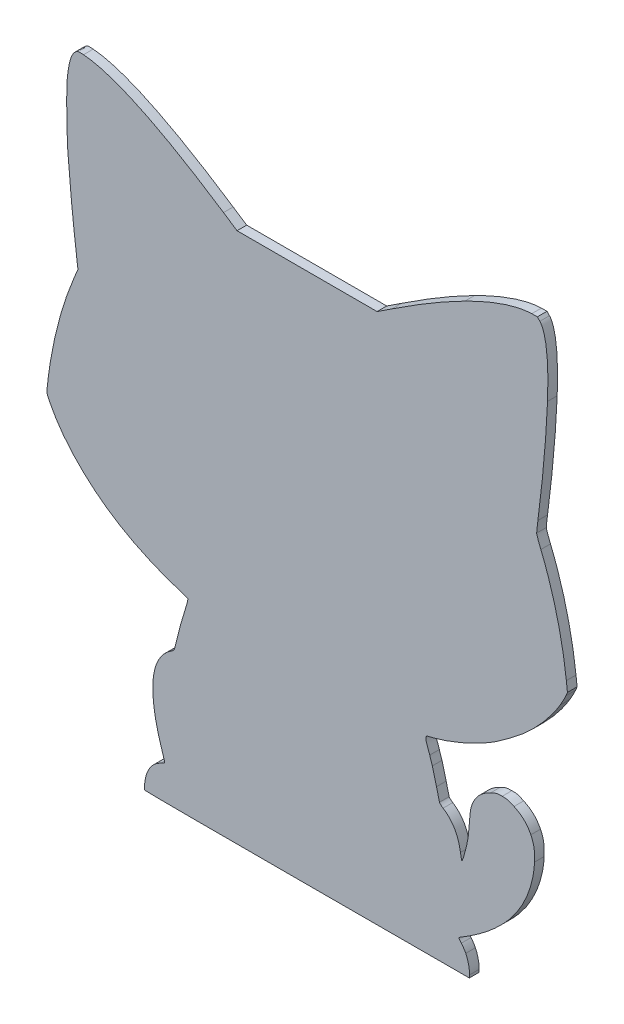
SolidWorks part; units mm, degrees
ref_plane "Front" through (0, 0, 0) normal (0, 0, 1) x (1, 0, 0)
ref_plane "Top" through (0, 0, 0) normal (0, 1, 0) x (1, 0, 0)
ref_plane "Right" through (0, 0, 0) normal (1, 0, 0) x (0, 0, -1)
sketch "Layer_3_board_outline" plane through (0, 0, 0) normal (0, 0, 1) x (1, 0, 0)
  line L0 (10.9053, 66.9894) -> (11.5659, 68.5759)
  line L1 (11.5659, 68.5759) -> (11.4685, 69.3451)
  line L3 (35.3096, 88.4796) -> (37.5166, 87.0182)
  line L4 (37.5166, 87.0182) -> (48.9356, 87.0182)
  line L5 (48.9356, 87.0182) -> (60.3546, 87.0182)
  line L6 (60.3546, 87.0182) -> (62.78, 88.6113)
  line L8 (85.5745, 99.329) -> (86.4912, 99.3449)
  line L9 (86.4912, 99.3449) -> (86.894, 98.9141)
  line L11 (91.2192, 50.3286) -> (91.3952, 48.7468)
  line L12 (91.3952, 48.7468) -> (91.1586, 48.1639)
  line L14 (71.6522, 32.0554) -> (70.4053, 31.6632)
  line L16 (75.4324, 0.8747) -> (75.3997, 0.419)
  line L17 (75.3997, 0.419) -> (48.9694, 0.3927)
  spline S0 degree 3 poles (22.5543, 2.0915) (22.8743, 3.7639) (23.7352, 4.9669) (25.0536, 5.5838) knots 0 0 0 0 1 1 1 1
  spline S1 degree 3 poles (25.0536, 5.5838) (25.4249, 5.7576) (25.7287, 5.9564) (25.7287, 6.0256) knots 0 0 0 0 1 1 1 1
  spline S2 degree 3 poles (25.7287, 6.0256) (25.7287, 6.0948) (25.5632, 6.6404) (25.3609, 7.238) knots 0 0 0 0 1 1 1 1
  spline S3 degree 3 poles (25.3609, 7.238) (25.1586, 7.8357) (24.8564, 8.8396) (24.6894, 9.469) knots 0 0 0 0 1 1 1 1
  spline S4 degree 3 poles (24.6894, 9.469) (22.9907, 15.8686) (23.6624, 20.1728) (26.6795, 22.2217) knots 0 0 0 0 1 1 1 1
  spline S5 degree 3 poles (26.6795, 22.2217) (27.344, 22.6729) (27.2709, 22.5103) (27.7511, 24.6043) knots 0 0 0 0 1 1 1 1
  spline S6 degree 3 poles (27.7511, 24.6043) (28.0842, 26.057) (28.3922, 27.1563) (29.0736, 29.3246) knots 0 0 0 0 1 1 1 1
  spline S7 degree 3 poles (29.0736, 29.3246) (29.3591, 30.233) (29.5542, 31.0103) (29.5071, 31.0519) knots 0 0 0 0 1 1 1 1
  spline S8 degree 3 poles (29.5071, 31.0519) (29.4601, 31.0936) (28.7194, 31.3501) (27.8612, 31.622) knots 0 0 0 0 1 1 1 1
  spline S9 degree 3 poles (27.8612, 31.622) (23.6426, 32.9585) (19.3544, 35.0396) (16.2626, 37.251) knots 0 0 0 0 1 1 1 1
  spline S10 degree 3 poles (16.2626, 37.251) (12.0986, 40.2293) (8.7842, 43.8871) (7.0331, 47.4367) knots 0 0 0 0 1 1 1 1
  spline S11 degree 3 poles (7.0331, 47.4367) (6.4891, 48.5393) (6.4706, 48.6047) (6.5317, 49.2058) knots 0 0 0 0 1 1 1 1
  spline S12 degree 3 poles (6.5317, 49.2058) (7.1759, 55.5391) (8.6742, 61.6314) (10.9053, 66.9894) knots 0 0 0 0 1 1 1 1
  spline S13 degree 3 poles (11.4685, 69.3451) (10.7624, 74.9222) (10.3512, 78.9367) (9.9139, 84.5216) knots 0 0 0 0 1 1 1 1
  spline S14 degree 3 poles (9.9139, 84.5216) (9.7349, 86.8074) (9.6665, 92.8149) (9.8014, 94.4038) knots 0 0 0 0 1 1 1 1
  spline S15 degree 3 poles (9.8014, 94.4038) (10.0299, 97.0971) (10.5123, 98.6644) (11.2695, 99.1737) knots 0 0 0 0 1 1 1 1
  spline S16 degree 3 poles (11.2695, 99.1737) (11.6019, 99.3972) (11.7071, 99.4131) (12.4782, 99.3562) knots 0 0 0 0 1 1 1 1
  spline S17 degree 3 poles (12.4782, 99.3562) (17.2568, 99.0032) (24.9562, 95.3353) (35.3096, 88.4796) knots 0 0 0 0 1 1 1 1
  spline S18 degree 3 poles (62.78, 88.6113) (67.6195, 91.7902) (70.9778, 93.7789) (74.6716, 95.6533) knots 0 0 0 0 1 1 1 1
  spline S19 degree 3 poles (74.6716, 95.6533) (79.313, 98.0086) (83.1023, 99.286) (85.5745, 99.329) knots 0 0 0 0 1 1 1 1
  spline S20 degree 3 poles (86.894, 98.9141) (87.9393, 97.7962) (88.385, 94.0098) (88.1512, 88.2336) knots 0 0 0 0 1 1 1 1
  spline S21 degree 3 poles (88.1512, 88.2336) (87.9441, 83.1197) (87.364, 76.6222) (86.5798, 70.6345) knots 0 0 0 0 1 1 1 1
  spline S22 degree 3 poles (86.5798, 70.6345) (86.4674, 69.7763) (86.3752, 68.9237) (86.3748, 68.7398) knots 0 0 0 0 1 1 1 1
  spline S23 degree 3 poles (86.3748, 68.7398) (86.3745, 68.5559) (86.6813, 67.6681) (87.0565, 66.7668) knots 0 0 0 0 1 1 1 1
  spline S24 degree 3 poles (87.0565, 66.7668) (89.0657, 61.9419) (90.602, 55.875) (91.2192, 50.3286) knots 0 0 0 0 1 1 1 1
  spline S25 degree 3 poles (91.1586, 48.1639) (91.0285, 47.8433) (90.5978, 47.0338) (90.2015, 46.3649) knots 0 0 0 0 1 1 1 1
  spline S26 degree 3 poles (90.2015, 46.3649) (88.3612, 43.2589) (85.3637, 40.0375) (82.1396, 37.7007) knots 0 0 0 0 1 1 1 1
  spline S27 degree 3 poles (82.1396, 37.7007) (81.5556, 37.2774) (80.7888, 36.7204) (80.4357, 36.4629) knots 0 0 0 0 1 1 1 1
  spline S28 degree 3 poles (80.4357, 36.4629) (79.3811, 35.6941) (78.2868, 35.0378) (76.8646, 34.3211) knots 0 0 0 0 1 1 1 1
  spline S29 degree 3 poles (76.8646, 34.3211) (75.1759, 33.4267) (73.4397, 32.6819) (71.6522, 32.0554) knots 0 0 0 0 1 1 1 1
  spline S30 degree 3 poles (70.4053, 31.6632) (69.7195, 31.4475) (68.9243, 31.2338) (68.6382, 31.1884) knots 0 0 0 0 1 1 1 1
  spline S31 degree 3 poles (68.6382, 31.1884) (67.9304, 31.0665) (68.5596, 29.7193) (68.94, 28.679) knots 0 0 0 0 1 1 1 1
  spline S32 degree 3 poles (68.94, 28.679) (68.9683, 28.4555) (69.2248, 27.8183) (69.3642, 27.3601) knots 0 0 0 0 1 1 1 1
  spline S33 degree 3 poles (69.3642, 27.3601) (69.5037, 26.9019) (69.8097, 25.7317) (70.0443, 24.7595) knots 0 0 0 0 1 1 1 1
  spline S34 degree 3 poles (70.0443, 24.7595) (70.2788, 23.7874) (70.4956, 22.9068) (70.526, 22.8027) knots 0 0 0 0 1 1 1 1
  spline S35 degree 3 poles (70.526, 22.8027) (70.5564, 22.6986) (70.8228, 22.457) (71.1181, 22.266) knots 0 0 0 0 1 1 1 1
  spline S36 degree 3 poles (71.1181, 22.266) (72.6744, 21.2587) (73.5873, 19.7014) (73.9538, 17.4287) knots 0 0 0 0 1 1 1 1
  spline S37 degree 3 poles (73.9538, 17.4287) (74.0412, 16.8863) (74.1326, 16.4227) (74.1568, 16.3985) knots 0 0 0 0 1 1 1 1
  spline S38 degree 3 poles (74.1568, 16.3985) (74.3156, 16.2397) (75.0624, 19.0086) (75.2337, 20.3914) knots 0 0 0 0 1 1 1 1
  spline S39 degree 3 poles (75.2337, 20.3914) (75.2975, 20.9063) (75.3914, 21.9859) (75.4424, 22.7904) knots 0 0 0 0 1 1 1 1
  spline S40 degree 3 poles (75.4424, 22.7904) (75.5123, 23.8944) (75.5975, 24.4329) (75.7897, 24.9855) knots 0 0 0 0 1 1 1 1
  spline S41 degree 3 poles (75.7897, 24.9855) (76.3222, 26.5169) (77.2683, 27.5376) (78.8636, 28.3018) knots 0 0 0 0 1 1 1 1
  spline S42 degree 3 poles (78.8636, 28.3018) (79.7849, 28.7432) (79.875, 28.7652) (80.7569, 28.7652) knots 0 0 0 0 1 1 1 1
  spline S43 degree 3 poles (80.7569, 28.7652) (81.6424, 28.7652) (81.7267, 28.7444) (82.6855, 28.2872) knots 0 0 0 0 1 1 1 1
  spline S44 degree 3 poles (82.6855, 28.2872) (84.0184, 27.6517) (84.8444, 26.8593) (85.4246, 25.6593) knots 0 0 0 0 1 1 1 1
  spline S45 degree 3 poles (85.4246, 25.6593) (85.9548, 24.563) (86.1083, 23.6615) (86.0304, 22.1023) knots 0 0 0 0 1 1 1 1
  spline S46 degree 3 poles (86.0304, 22.1023) (85.8531, 18.5534) (84.4733, 15.1028) (82.0199, 12.0731) knots 0 0 0 0 1 1 1 1
  spline S47 degree 3 poles (82.0199, 12.0731) (81.1603, 11.0116) (79.5673, 9.456) (78.2886, 8.4295) knots 0 0 0 0 1 1 1 1
  spline S48 degree 3 poles (78.2886, 8.4295) (77.2107, 7.564) (75.046, 6.0753) (74.1255, 5.5662) knots 0 0 0 0 1 1 1 1
  spline S49 degree 3 poles (74.1255, 5.5662) (73.8823, 5.4318) (73.6834, 5.2771) (73.6834, 5.2225) knots 0 0 0 0 1 1 1 1
  spline S50 degree 3 poles (73.6834, 5.2225) (73.6834, 5.1679) (73.8679, 4.923) (74.0935, 4.6783) knots 0 0 0 0 1 1 1 1
  spline S51 degree 3 poles (74.0935, 4.6783) (74.3191, 4.4335) (74.644, 3.9554) (74.8154, 3.6158) knots 0 0 0 0 1 1 1 1
  spline S52 degree 3 poles (74.8154, 3.6158) (75.173, 2.9074) (75.4802, 1.5425) (75.4324, 0.8747) knots 0 0 0 0 1 1 1 1
  spline S53 degree 3 poles (48.9694, 0.3927) (34.4327, 0.3783) (22.5078, 0.3978) (22.4315, 0.4741) knots 0 0 0 0 1 1 1 1
  spline S54 degree 3 poles (22.4315, 0.4741) (22.3552, 0.5504) (22.3902, 1.2336) (22.5543, 2.0915) knots 0 0 0 0 1 1 1 1
sketch "Layer_3_board_outline_dog" plane through (0, 0, 0) normal (0, 0, 1) x (1, 0, 0)
  line L0 (34.5113, 86.8831) -> (37.5166, 87.0182)
  line L1 (37.5166, 87.0182) -> (48.9356, 87.0182)
  line L2 (48.9356, 87.0182) -> (60.3546, 87.0182)
  line L3 (60.3546, 87.0182) -> (63.4286, 86.965)
  line L6 (70.4053, 31.6632) -> (71.6522, 32.0554)
  line L7 (75.4324, 0.8747) -> (75.3997, 0.419)
  line L8 (75.3997, 0.419) -> (48.9694, 0.3927)
  spline S0 degree 3 poles (22.5543, 2.0915) (22.8743, 3.7639) (23.7352, 4.9669) (25.0536, 5.5838) knots 0 0 0 0 1 1 1 1
  spline S1 degree 3 poles (25.0536, 5.5838) (25.4249, 5.7576) (25.7287, 5.9564) (25.7287, 6.0256) knots 0 0 0 0 1 1 1 1
  spline S2 degree 3 poles (25.7287, 6.0256) (25.7287, 6.0948) (25.5632, 6.6404) (25.3609, 7.238) knots 0 0 0 0 1 1 1 1
  spline S3 degree 3 poles (25.3609, 7.238) (25.1586, 7.8357) (24.8564, 8.8396) (24.6894, 9.469) knots 0 0 0 0 1 1 1 1
  spline S4 degree 3 poles (24.6894, 9.469) (22.9907, 15.8686) (23.6624, 20.1728) (26.6795, 22.2217) knots 0 0 0 0 1 1 1 1
  spline S5 degree 3 poles (26.6795, 22.2217) (27.344, 22.6729) (27.2709, 22.5103) (27.7511, 24.6043) knots 0 0 0 0 1 1 1 1
  spline S6 degree 3 poles (27.7511, 24.6043) (28.0842, 26.057) (28.3922, 27.1563) (29.0736, 29.3246) knots 0 0 0 0 1 1 1 1
  spline S7 degree 3 poles (29.0736, 29.3246) (29.3591, 30.233) (29.5542, 31.0103) (29.5071, 31.0519) knots 0 0 0 0 1 1 1 1
  spline S8 degree 3 poles (29.5071, 31.0519) (29.4601, 31.0936) (28.7194, 31.3501) (27.8612, 31.622) knots 0 0 0 0 1 1 1 1
  spline S9 degree 3 poles (27.8612, 31.622) (23.6426, 32.9585) (19.3544, 35.0396) (16.2626, 37.251) knots 0 0 0 0 1 1 1 1
  spline S10 degree 3 poles (16.2626, 37.251) (14.8605, 38.2539) (13.5547, 39.3338) (12.3724, 40.4607) knots 0 0 0 0 1 1 1 1
  spline S11 degree 3 poles (12.3724, 40.4607) (8.0865, 44.7253) (6.6138, 52.6467) (8.3368, 59.3063) knots 0 0 0 0 1 1 1 1
  spline S12 degree 3 poles (8.3368, 59.3063) (9.0353, 61.9873) (9.8952, 64.5636) (10.9053, 66.9894) knots 0 0 0 0 1 1 1 1
  spline S13 degree 3 poles (10.9053, 66.9894) (11.5659, 68.7009) (12.4282, 70.3216) (13.2396, 71.9644) knots 0 0 0 0 1 1 1 1
  spline S14 degree 3 poles (13.2396, 71.9644) (11.7395, 75.6682) (10.3159, 79.8187) (9.9139, 84.5216) knots 0 0 0 0 1 1 1 1
  spline S15 degree 3 poles (9.9139, 84.5216) (9.7923, 85.9446) (9.6966, 88.8136) (9.7305, 91.1579) knots 0 0 0 0 1 1 1 1
  spline S16 degree 3 poles (9.7305, 91.1579) (9.762, 93.3288) (10.4659, 95.1894) (12.6101, 96.8277) knots 0 0 0 0 1 1 1 1
  spline S17 degree 3 poles (12.6101, 96.8277) (15.0948, 98.5292) (17.1938, 98.3272) (19.1427, 97.5385) knots 0 0 0 0 1 1 1 1
  spline S18 degree 3 poles (19.1427, 97.5385) (23.4634, 95.771) (29.639, 90.4894) (34.5113, 86.8831) knots 0 0 0 0 1 1 1 1
  spline S19 degree 3 poles (63.4286, 86.965) (67.6214, 90.0079) (71.6762, 93.3299) (74.7714, 95.4039) knots 0 0 0 0 1 1 1 1
  spline S20 degree 3 poles (74.7714, 95.4039) (76.1473, 96.3258) (77.5392, 97.0431) (78.8286, 97.5693) knots 0 0 0 0 1 1 1 1
  spline S21 degree 3 poles (78.8286, 97.5693) (81.5912, 98.6966) (83.8713, 97.6769) (85.2217, 96.9477) knots 0 0 0 0 1 1 1 1
  spline S22 degree 3 poles (85.2217, 96.9477) (88.0045, 95.2985) (88.2116, 91.8206) (88.2114, 90.8053) knots 0 0 0 0 1 1 1 1
  spline S23 degree 3 poles (88.2114, 90.8053) (88.2079, 89.9989) (88.1879, 89.1408) (88.1512, 88.2336) knots 0 0 0 0 1 1 1 1
  spline S24 degree 3 poles (88.1512, 88.2336) (87.9441, 83.1197) (86.7154, 76.7219) (84.7838, 72.0315) knots 0 0 0 0 1 1 1 1
  spline S25 degree 3 poles (84.7838, 72.0315) (85.5478, 70.3015) (86.3982, 68.3577) (87.0565, 66.7668) knots 0 0 0 0 1 1 1 1
  spline S26 degree 3 poles (87.0565, 66.7668) (88.0096, 64.478) (88.8563, 61.9098) (89.5489, 59.2502) knots 0 0 0 0 1 1 1 1
  spline S27 degree 3 poles (89.5489, 59.2502) (91.2047, 53.4038) (89.9888, 44.7358) (85.3831, 40.4187) knots 0 0 0 0 1 1 1 1
  spline S28 degree 3 poles (85.3831, 40.4187) (84.3555, 39.4337) (83.2613, 38.5137) (82.1396, 37.7007) knots 0 0 0 0 1 1 1 1
  spline S29 degree 3 poles (82.1396, 37.7007) (81.5556, 37.2774) (80.7888, 36.7204) (80.4357, 36.4629) knots 0 0 0 0 1 1 1 1
  spline S30 degree 3 poles (80.4357, 36.4629) (79.3811, 35.6941) (78.2868, 35.0378) (76.8646, 34.3211) knots 0 0 0 0 1 1 1 1
  spline S31 degree 3 poles (76.8646, 34.3211) (75.1759, 33.4267) (73.4397, 32.6819) (71.6522, 32.0554) knots 0 0 0 0 1 1 1 1
  spline S32 degree 3 poles (70.4053, 31.6632) (69.7195, 31.4475) (68.9243, 31.2338) (68.6382, 31.1884) knots 0 0 0 0 1 1 1 1
  spline S33 degree 3 poles (68.6382, 31.1884) (67.9304, 31.0665) (68.5596, 29.7193) (68.94, 28.679) knots 0 0 0 0 1 1 1 1
  spline S34 degree 3 poles (68.94, 28.679) (68.9683, 28.4555) (69.2248, 27.8183) (69.3642, 27.3601) knots 0 0 0 0 1 1 1 1
  spline S35 degree 3 poles (69.3642, 27.3601) (69.5037, 26.9019) (69.8097, 25.7317) (70.0443, 24.7595) knots 0 0 0 0 1 1 1 1
  spline S36 degree 3 poles (70.0443, 24.7595) (70.2788, 23.7874) (70.4956, 22.9068) (70.526, 22.8027) knots 0 0 0 0 1 1 1 1
  spline S37 degree 3 poles (70.526, 22.8027) (70.5564, 22.6986) (70.8228, 22.457) (71.1181, 22.266) knots 0 0 0 0 1 1 1 1
  spline S38 degree 3 poles (71.1181, 22.266) (72.6744, 21.2587) (73.5873, 19.7014) (73.9538, 17.4287) knots 0 0 0 0 1 1 1 1
  spline S39 degree 3 poles (73.9538, 17.4287) (74.0412, 16.8863) (74.1326, 16.4227) (74.1568, 16.3985) knots 0 0 0 0 1 1 1 1
  spline S40 degree 3 poles (74.1568, 16.3985) (74.3156, 16.2397) (75.0624, 19.0086) (75.2337, 20.3914) knots 0 0 0 0 1 1 1 1
  spline S41 degree 3 poles (75.2337, 20.3914) (75.2975, 20.9063) (75.3914, 21.9859) (75.4424, 22.7904) knots 0 0 0 0 1 1 1 1
  spline S42 degree 3 poles (75.4424, 22.7904) (75.5123, 23.8944) (75.5975, 24.4329) (75.7897, 24.9855) knots 0 0 0 0 1 1 1 1
  spline S43 degree 3 poles (75.7897, 24.9855) (76.3222, 26.5169) (77.2683, 27.5376) (78.8636, 28.3018) knots 0 0 0 0 1 1 1 1
  spline S44 degree 3 poles (78.8636, 28.3018) (79.7849, 28.7432) (79.875, 28.7652) (80.7569, 28.7652) knots 0 0 0 0 1 1 1 1
  spline S45 degree 3 poles (80.7569, 28.7652) (81.6424, 28.7652) (81.7267, 28.7444) (82.6855, 28.2872) knots 0 0 0 0 1 1 1 1
  spline S46 degree 3 poles (82.6855, 28.2872) (84.0184, 27.6517) (84.8444, 26.8593) (85.4246, 25.6593) knots 0 0 0 0 1 1 1 1
  spline S47 degree 3 poles (85.4246, 25.6593) (85.9548, 24.563) (86.1083, 23.6615) (86.0304, 22.1023) knots 0 0 0 0 1 1 1 1
  spline S48 degree 3 poles (86.0304, 22.1023) (85.8531, 18.5534) (84.4733, 15.1028) (82.0199, 12.0731) knots 0 0 0 0 1 1 1 1
  spline S49 degree 3 poles (82.0199, 12.0731) (81.1603, 11.0116) (79.5673, 9.456) (78.2886, 8.4295) knots 0 0 0 0 1 1 1 1
  spline S50 degree 3 poles (78.2886, 8.4295) (77.2107, 7.564) (75.046, 6.0753) (74.1255, 5.5662) knots 0 0 0 0 1 1 1 1
  spline S51 degree 3 poles (74.1255, 5.5662) (73.8823, 5.4318) (73.6834, 5.2771) (73.6834, 5.2225) knots 0 0 0 0 1 1 1 1
  spline S52 degree 3 poles (73.6834, 5.2225) (73.6834, 5.1679) (73.8679, 4.923) (74.0935, 4.6783) knots 0 0 0 0 1 1 1 1
  spline S53 degree 3 poles (74.0935, 4.6783) (74.3191, 4.4335) (74.644, 3.9554) (74.8154, 3.6158) knots 0 0 0 0 1 1 1 1
  spline S54 degree 3 poles (74.8154, 3.6158) (75.173, 2.9074) (75.4802, 1.5425) (75.4324, 0.8747) knots 0 0 0 0 1 1 1 1
  spline S55 degree 3 poles (48.9694, 0.3927) (34.4327, 0.3783) (22.5078, 0.3978) (22.4315, 0.4741) knots 0 0 0 0 1 1 1 1
  spline S56 degree 3 poles (22.4315, 0.4741) (22.3552, 0.5504) (22.3902, 1.2336) (22.5543, 2.0915) knots 0 0 0 0 1 1 1 1
extrude "Boss-Extrude1" add sketch "Layer_3_board_outline" along normal blind 1.5748
extrude "Boss-Extrude2" [suppressed] add sketch "Layer_3_board_outline_dog" along normal blind 1.5748 separate body
